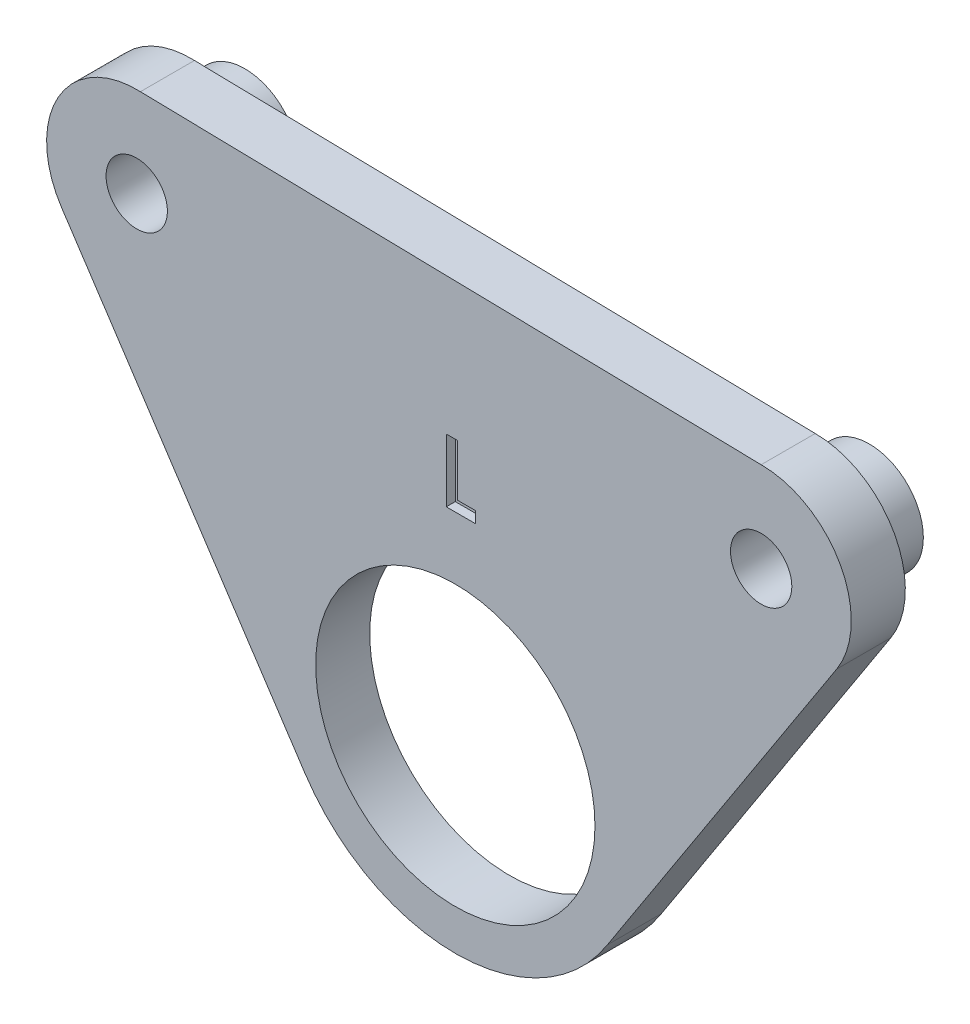
SolidWorks part; units mm, degrees
ref_plane "Front Plane" through (0, 0, 0) normal (0, 0, 1) x (1, 0, 0)
ref_plane "Top Plane" through (0, 0, 0) normal (0, 1, 0) x (1, 0, 0)
ref_plane "Right Plane" through (0, 0, 0) normal (1, 0, 0) x (0, 0, -1)
sketch "Sketch1" plane through (0, 0, 0) normal (0, 0, 1) x (1, 0, 0)
  line L0 (0, 0) -> (0, -44.3691) construction
  line L1 (0, 0) -> (0, 32.675) construction
  line L2 (0, -44.3691) -> (-72.2288, 27.8597) construction
  line L3 (0, 0) -> (-40.7025, -40.7025) construction
  line L4 (0, 0) -> (33.9411, 33.9411) construction
  line L5 (0, 0) -> (-35.3553, 35.3553) construction
  line L6 (-21.8489, 14.9207) -> (-8.3424, -5.514)
  line L7 (-17.4737, 22.6735) -> (16.9706, 21.9706)
  line L8 (8.4349, -5.3714) -> (21.165, 14.2491)
  circle A0 centre (0, 0) radius 7.75
  arc A1 (-8.3424, -5.514) -> (8.4349, -5.3714) centre (0, 0) ccw
  circle A2 centre (-17.6777, 17.6777) radius 1.7025
  circle A3 centre (16.9706, 16.9706) radius 1.7025
  circle A4 centre (-17.6777, 17.6777) radius 3
  circle A5 centre (16.9706, 16.9706) radius 3
  arc A6 (-17.4737, 22.6735) -> (-21.8489, 14.9207) centre (-17.6777, 17.6777) ccw
  arc A7 (21.165, 14.2491) -> (16.9706, 21.9706) centre (16.9706, 16.9706) ccw
  dimension "D1" = 15.5
  dimension "D2" = 20
  dimension "D4" = 3.405
  dimension "D6" = 3.405
  dimension "D7" = 6
  dimension "D8" = 6
  dimension "D9" = 10
  dimension "D10" = 10
  dimension "D3" = 25
  dimension "D5" = 24
extrude "Boss-Extrude3" add sketch "Sketch1" along normal blind 3 contours L8 A7 L7 A6 L6 A1 A0 A4 A5
sketch "Sketch3" plane through (0, 0, 3) normal (0, 0, 1) x (1, 0, 0)
  circle A0 centre (-17.6777, 17.6777) radius 3
  circle A1 centre (-17.6777, 17.6777) radius 1.7025
  circle A2 centre (16.9706, 16.9706) radius 3
  circle A3 centre (16.9706, 16.9706) radius 1.7025
  dimension "D1" = 3.405
  dimension "D2" = 3.405
extrude "Boss-Extrude4" add sketch "Sketch3" against normal blind 6
sketch "Sketch4" plane through (0, 0, 3) normal (0, 0, 1) x (1, 0, 0)
  text T0 "<b>L</b>"
extrude "Cut-Extrude1" cut sketch "Sketch4" against normal blind 0.5
